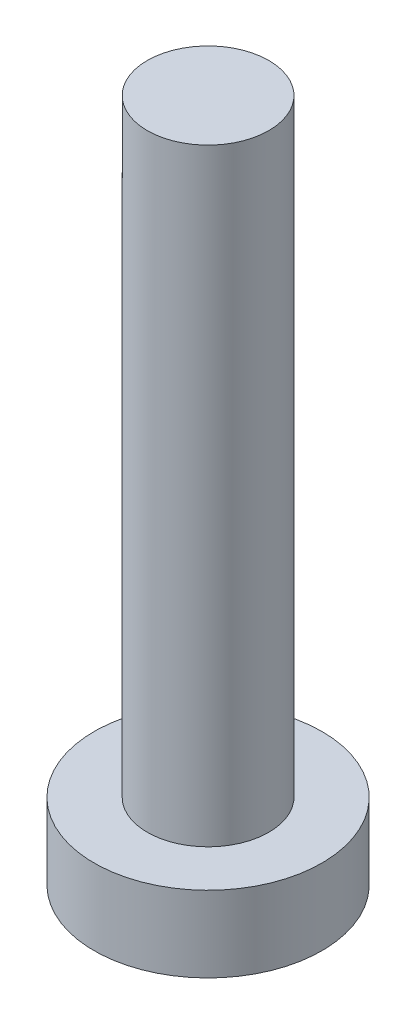
SolidWorks part; units mm, degrees
ref_plane "前基準面" through (0, 0, 0) normal (0, 0, 1) x (1, 0, 0)
ref_plane "上基準面" through (0, 0, 0) normal (0, 1, 0) x (1, 0, 0)
ref_plane "右基準面" through (0, 0, 0) normal (1, 0, 0) x (0, 0, -1)
sketch "草圖1" plane through (0, 0, 0) normal (0, 1, 0) x (1, 0, 0)
  circle A0 centre (0, 0) radius 4
  dimension "D1" = 8
extrude "填料-伸長1" add sketch "草圖1" along normal blind 40
sketch "草圖2" plane through (0, 0, 0) normal (0, -1, 0) x (-1, 0, 0)
  circle A0 centre (0, 0) radius 7.5
  dimension "D1" = 15
extrude "填料-伸長2" add sketch "草圖2" along normal blind 5
